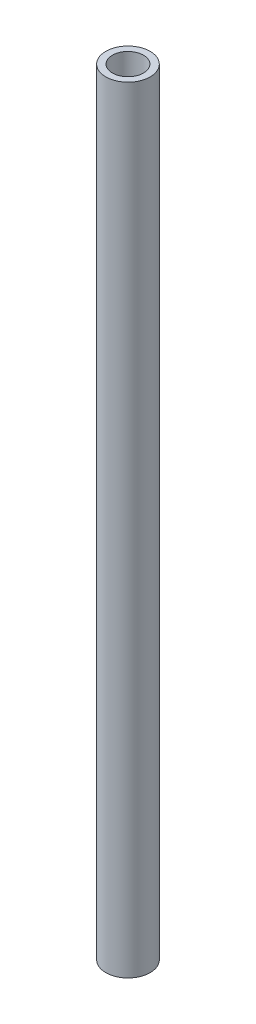
SolidWorks part; units mm, degrees
ref_plane "前视基准面" through (0, 0, 0) normal (0, 0, 1) x (1, 0, 0)
ref_plane "上视基准面" through (0, 0, 0) normal (0, 1, 0) x (1, 0, 0)
ref_plane "右视基准面" through (0, 0, 0) normal (1, 0, 0) x (0, 0, -1)
sketch "草图1" plane through (0, 0, 0) normal (0, 1, 0) x (1, 0, 0)
  circle A0 centre (0, 0) radius 10
  dimension "D1" = 20
extrude "拉伸-薄壁1" add sketch "草图1" along normal blind 350 thin thin type one direction reverse wall 3
